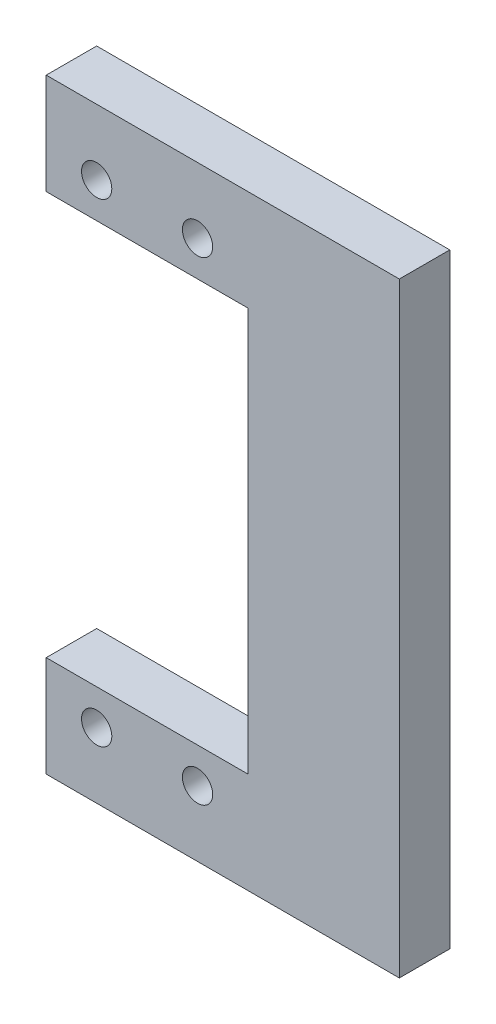
SolidWorks part; units mm, degrees
ref_plane "Plan de face" through (0, 0, 0) normal (0, 0, 1) x (1, 0, 0)
ref_plane "Plan de dessus" through (0, 0, 0) normal (0, 1, 0) x (1, 0, 0)
ref_plane "Plan de droite" through (0, 0, 0) normal (1, 0, 0) x (0, 0, -1)
sketch "Esquisse1" plane through (0, 0, 0) normal (0, 0, 1) x (1, 0, 0)
  line L0 (10, 50) -> (10, 10) construction
  line L1 (0, 0) -> (35, 0)
  line L2 (0, 0) -> (0, 10)
  line L3 (0, 60) -> (35, 60)
  line L4 (35, 0) -> (35, 60)
  line L5 (0, 10) -> (20, 10)
  line L7 (0, 50) -> (20, 50)
  line L8 (20, 10) -> (20, 50)
  line L9 (0, 30) -> (20, 30) construction
  line L10 (0, 50) -> (0, 60)
  circle A0 centre (5, 53.5) radius 1.5
  circle A1 centre (15, 53.5) radius 1.5
  circle A2 centre (15, 6.5) radius 1.5
  circle A3 centre (5, 6.5) radius 1.5
  dimension "D3" = 3.5
  dimension "D8" = 3
  dimension "D1" = 20
  dimension "D2" = 40
  dimension "D4" = 5
  dimension "D5" = 60
  dimension "D6" = 10
  dimension "D7" = 35
extrude "Boss.-Extru.1" add sketch "Esquisse1" along normal blind 5
